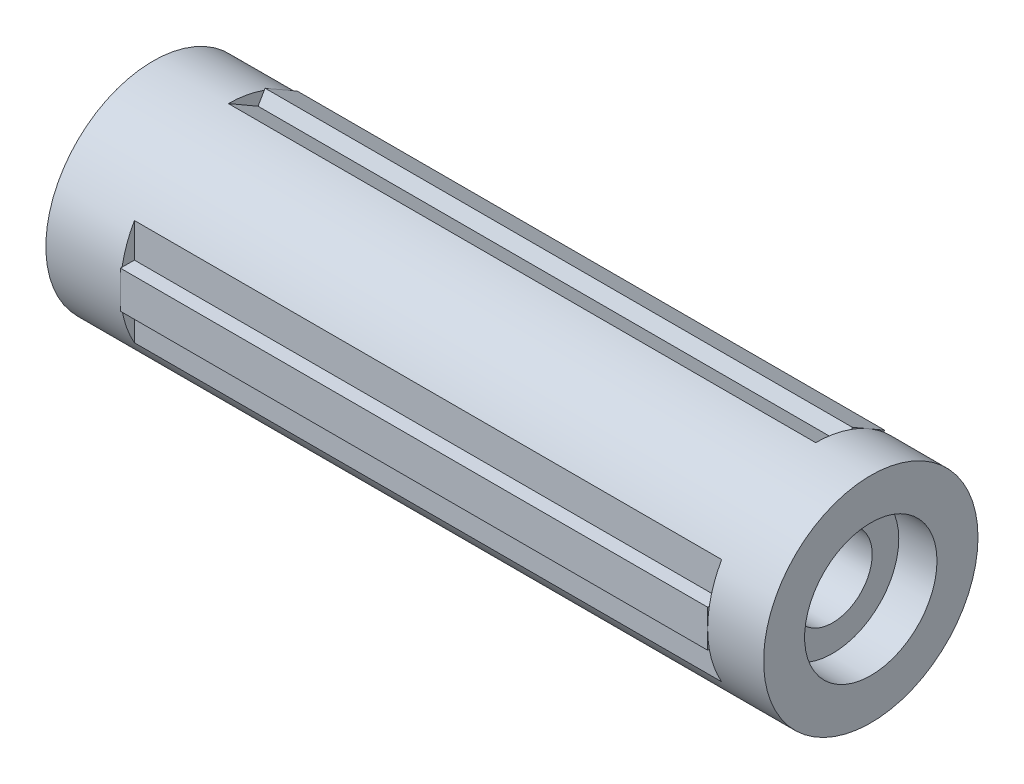
SolidWorks part; units mm, degrees
ref_plane "Ebene vorne" through (0, 0, 0) normal (0, 0, 1) x (1, 0, 0)
ref_plane "Ebene oben" through (0, 0, 0) normal (0, 1, 0) x (1, 0, 0)
ref_plane "Ebene rechts" through (0, 0, 0) normal (1, 0, 0) x (0, 0, -1)
sketch "Skizze1" plane through (0, 0, 0) normal (1, 0, 0) x (0, 0, -1)
  circle A0 centre (0, 0) radius 11.5
  dimension "D1" = 23
extrude "Aufsatz-Linear austragen1" add sketch "Skizze1" along normal blind 77
sketch "Skizze2" plane through (77, 0, 0) normal (1, 0, 0) x (0, 0, -1)
  circle A0 centre (0, 0) radius 7.1
  dimension "D1" = 14.2
extrude "Schnitt-Linear austragen1" cut sketch "Skizze2" against normal blind 4.1
sketch "Skizze3" plane through (72.9, 0, 0) normal (1, 0, 0) x (0, 0, -1)
  circle A0 centre (0, 0) radius 4.25
  dimension "D1" = 8.5
extrude "Schnitt-Linear austragen2" cut sketch "Skizze3" against normal blind 11
sketch "Skizze4" plane through (0, 0, 0) normal (-1, 0, 0) x (0, 0, 1)
  circle A0 centre (0, 0) radius 9.6
  dimension "D1" = 19.2
extrude "Schnitt-Linear austragen3" cut sketch "Skizze4" against normal blind 11.8
sketch "Skizze7" plane through (77, 0, 0) normal (1, 0, 0) x (0, 0, -1)
  line L0 (0, 13.4409) -> (0, -14.2481) construction
  line L1 (-11.5, 7.5) -> (-10, 7.5)
  line L2 (-11.5, 7.5) -> (-11.5, -7.5)
  line L3 (-11.5, -7.5) -> (-10, -7.5)
  line L4 (-10, 7.5) -> (-10, -7.5)
  point P7 (0, 0)
  point P11 (0, 0)
  dimension "D1" = 1.5
  dimension "D2" = 15
  dimension "D3" = 10
extrude "Schnitt-Linear austragen4" cut sketch "Skizze7" against normal blind 63 from offset 6 offset against normal yes
sketch "Skizze8" plane through (0, 0, 10) normal (0, 0, 1) x (1, 0, 0)
  line L0 (71, -5.6789) -> (71, 5.6789) construction
  line L1 (8, 2) -> (71, 2)
  line L2 (8, 2) -> (8, -2)
  line L3 (8, -2) -> (71, -2)
  line L4 (71, 2) -> (71, -2)
  line L5 (8, 2) -> (71, -2) construction
  line L6 (8, -2) -> (71, 2) construction
  line L7 (12.65, 0) -> (-12.65, 0) construction
  point P0 (39.5, 0)
  point P7 (0, 0)
  dimension "D1" = 31.5
  dimension "D3" = 63
  dimension "D4" = 4
extrude "Aufsatz-Linear austragen2" add sketch "Skizze8" along normal blind 1.5
sketch "Skizze10" plane through (11.8, 0, 0) normal (-1, 0, 0) x (0, 0, 1)
  line L1 (4.0389, -2.2407) -> (3.96, 2.3774)
  line L2 (3.96, 2.3774) -> (-0.0789, 4.6181)
  line L3 (-0.0789, 4.6181) -> (-4.0389, 2.2407)
  line L4 (-4.0389, 2.2407) -> (-3.96, -2.3774)
  line L5 (-3.96, -2.3774) -> (0.0789, -4.6181)
  line L6 (0.0789, -4.6181) -> (4.0389, -2.2407)
  circle A0 centre (0, 0) radius 4 construction
  dimension "D1" = 8
extrude "Schnitt-Linear austragen6" cut sketch "Skizze10" against normal blind 13.5
sketch "Skizze12" plane through (25.3, 0, 0) normal (-1, 0, 0) x (0, 0, 1)
  circle A0 centre (0, 0) radius 3
  dimension "D1" = 6
extrude "Schnitt-Linear austragen7" cut sketch "Skizze12" against normal blind 2
pattern_circular "Kreismuster3" count 3 over 360 about axis through (0, 0, 0) along (1, 0, 0) of "Aufsatz-Linear austragen2", "Schnitt-Linear austragen4"
